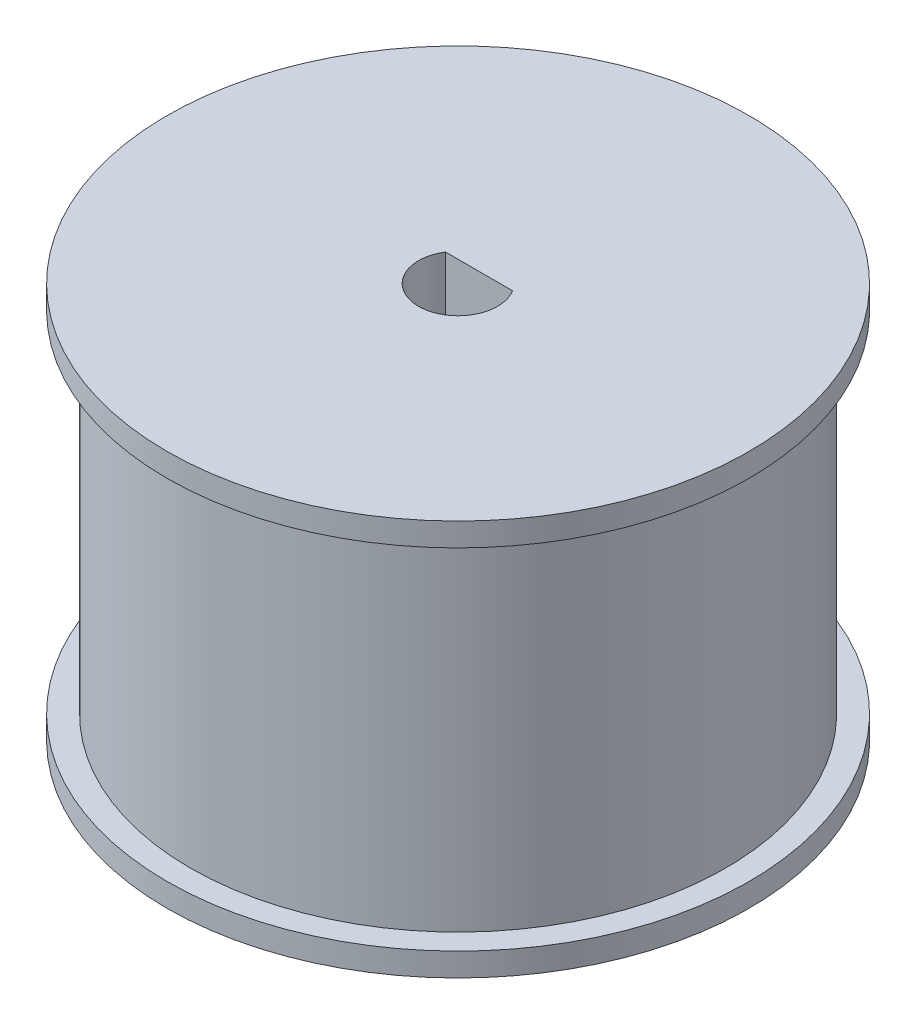
SolidWorks part; units mm, degrees
ref_plane "Plano frontal" through (0, 0, 0) normal (0, 0, 1) x (1, 0, 0)
ref_plane "Plano superior" through (0, 0, 0) normal (0, 1, 0) x (1, 0, 0)
ref_plane "Plano direito" through (0, 0, 0) normal (1, 0, 0) x (0, 0, -1)
sketch "Esboço1" plane through (0, 0, 0) normal (0, 1, 0) x (1, 0, 0)
  circle A0 centre (0, 0) radius 12.5
  dimension "D1" = 25
extrude "Ressalto-extrusão1" add sketch "Esboço1" along normal blind 1
sketch "Esboço2" plane through (0, 1, 0) normal (0, 1, 0) x (1, 0, 0)
  circle A0 centre (0, 0) radius 11.5
  dimension "D1" = 23
extrude "Ressalto-extrusão2" add sketch "Esboço2" along normal blind 15
sketch "Esboço3" plane through (0, 16, 0) normal (0, 1, 0) x (1, 0, 0)
  circle A0 centre (0, 0) radius 12.5
  dimension "D1" = 25
extrude "Ressalto-extrusão3" add sketch "Esboço3" along normal blind 1
sketch "Esboço4" plane through (0, 17, 0) normal (0, 1, 0) x (1, 0, 0)
  line L0 (0, -1.7) -> (0, 0.9)
  line L1 (0, 0.9) -> (-1.4422, 0.9)
  line L2 (-1.4422, 0.9) -> (1.4422, 0.9)
  circle A0 centre (0, 0) radius 1.7
  dimension "D1" = 3.4
  dimension "D2" = 2.6
extrude "Corte-extrusão1" cut sketch "Esboço4" against normal blind 12 contours L1 A0 L0 | L0 A0 L2
sketch "Esboço6" plane through (0, 0, 0) normal (0, 0, 1) x (1, 0, 0)
  line L0 (0, 0) -> (0, 17)
  line L1 (12.5, 17) -> (-12.5, 17) construction
  line L2 (0, 17) -> (0, 13)
  circle A0 centre (0, 13) radius 1.5
  dimension "D2" = 3
  dimension "D1" = 4
extrude "Corte-extrusão2" cut sketch "Esboço6" against normal blind 35 contours L0 A0 | L0 A0
sketch "Esboço7" plane through (0, 0, 0) normal (0, 0, 1) x (1, 0, 0)
  line L0 (0, 17) -> (0, 13)
  line L1 (12.5, 17) -> (-12.5, 17) construction
  circle A0 centre (0, 13) radius 2.75
  dimension "D2" = 5.5
  dimension "D1" = 4
extrude "Corte-extrusão3" cut sketch "Esboço7" against normal blind 35 from offset 5 contours A0 offset against normal yes
sketch "Esboço8" plane through (0, 0, 0) normal (0, -1, 0) x (-1, 0, 0)
  circle A0 centre (0, 0) radius 9.5
  dimension "D1" = 19
extrude "Corte-extrusão4" cut sketch "Esboço8" against normal blind 11
sketch "Esboço9" plane through (0, 11, 0) normal (0, -1, 0) x (1, 0, 0)
  line L1 (-2.9, -1.4503) -> (2.9, -1.4503)
  line L2 (-2.9, -1.4503) -> (-2.9, -3.9503)
  line L3 (-2.9, -3.9503) -> (2.9, -3.9503)
  line L4 (2.9, -1.4503) -> (2.9, -3.9503)
  line L5 (-2.9, -1.4503) -> (2.9, -3.9503) construction
  line L6 (-2.9, -3.9503) -> (2.9, -1.4503) construction
  point P0 (0, -2.7003)
  point P5 (0, 0)
  dimension "D1" = 5.8
  dimension "D2" = 2.5
extrude "Corte-extrusão5" cut sketch "Esboço9" against normal blind 4.8
